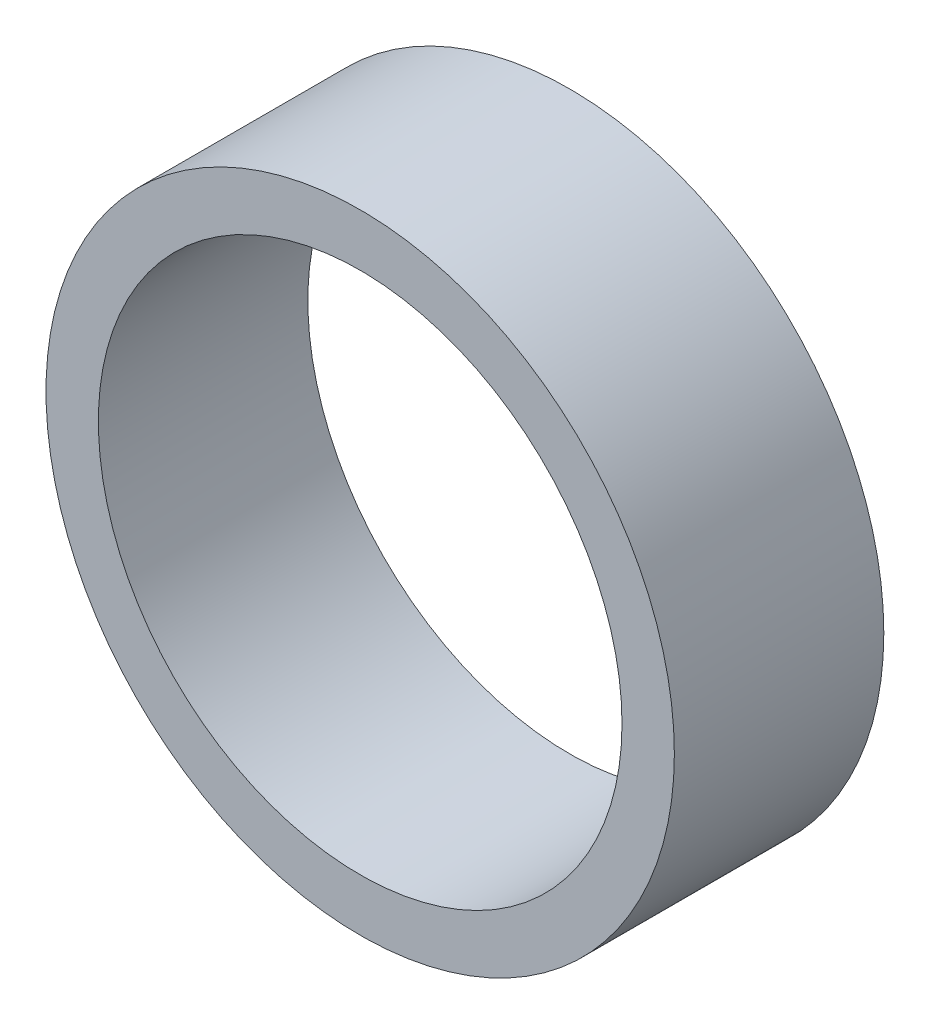
SolidWorks part; units mm, degrees
ref_plane "前视基准面" through (0, 0, 0) normal (0, 0, 1) x (1, 0, 0)
ref_plane "上视基准面" through (0, 0, 0) normal (0, 1, 0) x (1, 0, 0)
ref_plane "右视基准面" through (0, 0, 0) normal (1, 0, 0) x (0, 0, -1)
sketch "草图1" plane through (0, 0, 0) normal (0, 0, 1) x (1, 0, 0)
  circle A0 centre (0, 0) radius 2.5
  circle A1 centre (0, 0) radius 3
  point P4 (0, 0)
  dimension "D1" = 5
  dimension "D2" = 6
extrude "凸台-拉伸1" add sketch "草图1" along normal blind 2
